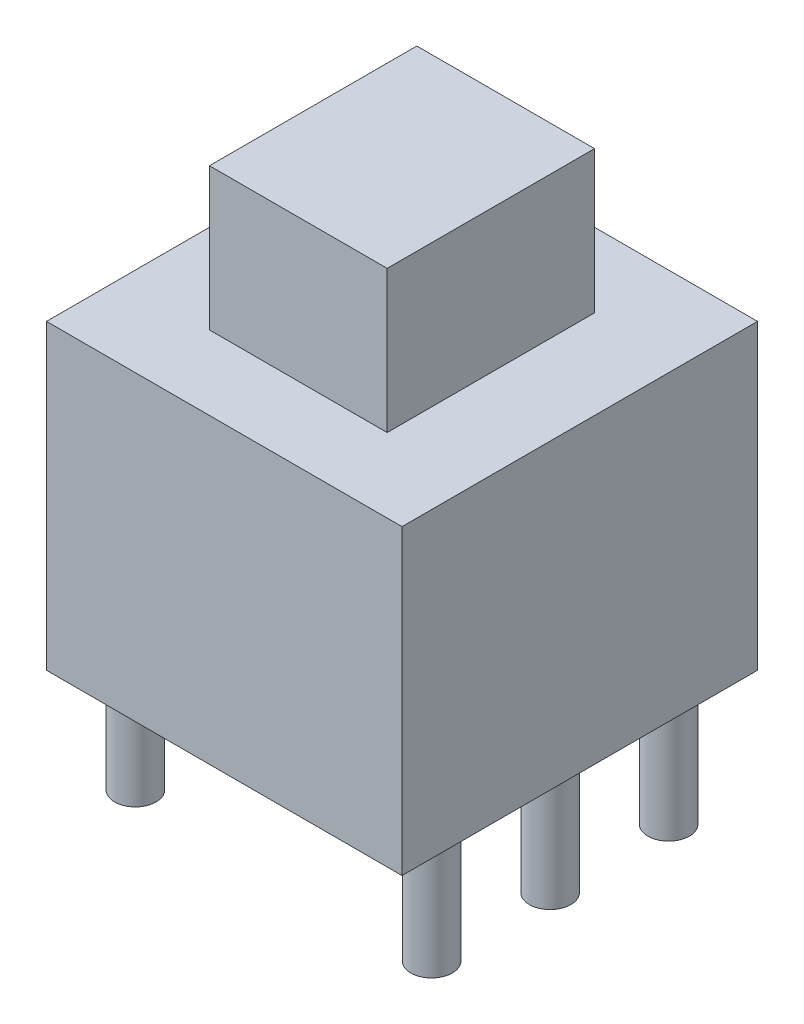
SolidWorks part; units mm, degrees
ref_plane "Front Plane" through (0, 0, 0) normal (0, 0, 1) x (1, 0, 0)
ref_plane "Top Plane" through (0, 0, 0) normal (0, 1, 0) x (1, 0, 0)
ref_plane "Right Plane" through (0, 0, 0) normal (1, 0, 0) x (0, 0, -1)
sketch "Sketch1" plane through (0, 0, 0) normal (0, 1, 0) x (1, 0, 0)
  line L1 (-3, -3) -> (3, -3)
  line L2 (-3, -3) -> (-3, 3)
  line L3 (-3, 3) -> (3, 3)
  line L4 (3, -3) -> (3, 3)
  line L5 (-3, -3) -> (3, 3) construction
  line L6 (-3, 3) -> (3, -3) construction
  point P0 (0, 0)
  dimension "D1" = 6
extrude "Boss-Extrude1" add sketch "Sketch1" along normal blind 5.1
sketch "Sketch2" plane through (0, 5.1, 0) normal (0, 1, 0) x (1, 0, 0)
  line L1 (-1.5, -1.75) -> (1.5, -1.75)
  line L2 (-1.5, -1.75) -> (-1.5, 1.75)
  line L3 (-1.5, 1.75) -> (1.5, 1.75)
  line L4 (1.5, -1.75) -> (1.5, 1.75)
  line L5 (-1.5, -1.75) -> (1.5, 1.75) construction
  line L6 (-1.5, 1.75) -> (1.5, -1.75) construction
  point P0 (0, 0)
  dimension "D1" = 3
  dimension "D2" = 3.5
extrude "Boss-Extrude2" add sketch "Sketch2" along normal blind 2.4
sketch "Sketch3" plane through (0, 0, 0) normal (0, -1, 0) x (1, 0, 0)
  line L0 (0, 3) -> (0, -3) construction
  line L1 (-3, 3) -> (3, 3) construction
  line L2 (3, -3) -> (-3, -3) construction
  line L3 (-2.5, 2) -> (-2.5, 0) construction
  line L4 (-2.5, 0) -> (-2.5, -2) construction
  circle A0 centre (-2.5, 0) radius 0.35
  circle A1 centre (-2.5, -2) radius 0.35
  circle A2 centre (-2.5, 2) radius 0.35
  circle A3 centre (2.5, -2) radius 0.35
  circle A4 centre (2.5, 0) radius 0.35
  circle A5 centre (2.5, 2) radius 0.35
  dimension "D1" = 0.7
  dimension "D2" = 2
  dimension "D3" = 5
extrude "Boss-Extrude3" add sketch "Sketch3" along normal blind 2
